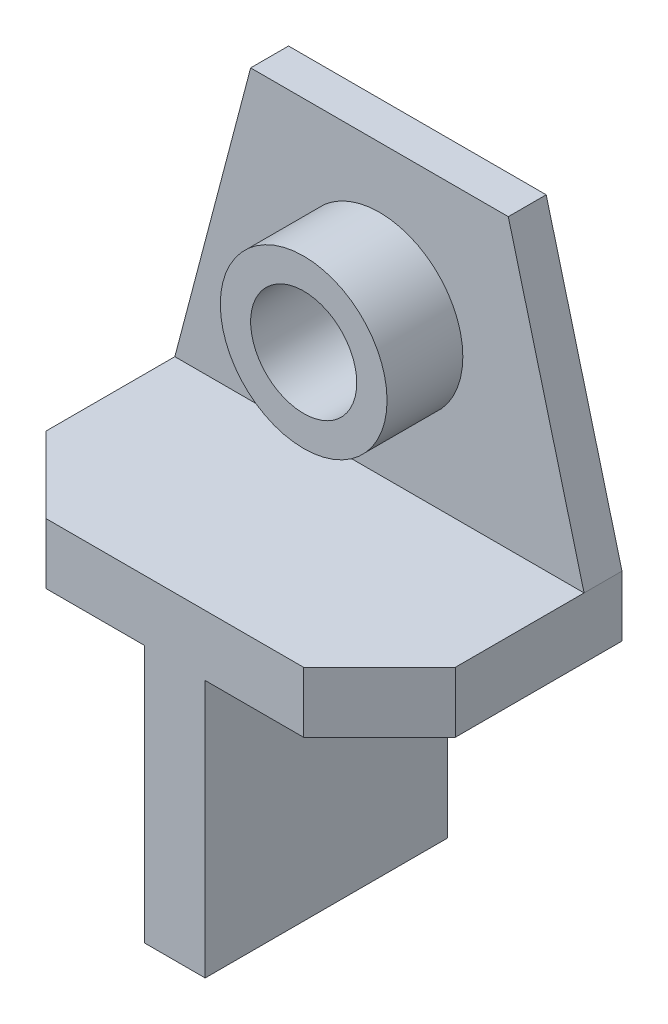
SolidWorks part; units mm, degrees
ref_plane "Front Plane" through (0, 0, 0) normal (0, 0, 1) x (1, 0, 0)
ref_plane "Top Plane" through (0, 0, 0) normal (0, 1, 0) x (1, 0, 0)
ref_plane "Right Plane" through (0, 0, 0) normal (1, 0, 0) x (0, 0, -1)
sketch "Sketch1" plane through (0, 0, 0) normal (0, 0, 1) x (1, 0, 0)
  line L0 (0, 0) -> (54, 0)
  line L1 (54, 0) -> (54, -8)
  line L2 (54, -8) -> (31, -8)
  line L3 (31, -8) -> (31, -42)
  line L4 (31, -42) -> (23, -42)
  line L5 (23, -42) -> (23, -8)
  line L6 (23, -8) -> (0, -8)
  line L7 (0, -8) -> (0, 0)
  point P3 (0, 0)
  point P10 (27, 0)
  point P11 (27, -42)
  dimension "D1" = 54
  dimension "D2" = 8
  dimension "D3" = 34
  dimension "D4" = 8
extrude "Boss-Extrude1" add sketch "Sketch1" along normal mid plane 32
sketch "Sketch2" plane through (0, 0, 16) normal (0, 0, 1) x (1, 0, 0)
  line L0 (0, 0) -> (10, 0)
  line L1 (54, 0) -> (0, 0) construction
  line L2 (10, 0) -> (10, -8)
  line L3 (0, -8) -> (23, -8) construction
  line L4 (10, -8) -> (0, -8)
  line L5 (0, -8) -> (0, 0)
  line L6 (54, 0) -> (44, 0)
  line L7 (44, 0) -> (44, -8)
  line L8 (31, -8) -> (54, -8) construction
  line L9 (44, -8) -> (54, -8)
  line L10 (54, -8) -> (54, 0)
  dimension "D1" = 10
  dimension "D2" = 10
extrude "Cut-Extrude1" [suppressed] cut sketch "Sketch2" against normal blind 10
sketch "Sketch3" plane through (0, 0, 0) normal (0, 1, 0) x (1, 0, 0)
  line L0 (0, 16) -> (54, 16)
  line L1 (54, 16) -> (0, 16) construction
  line L2 (54, 16) -> (54, 11)
  line L3 (54, -16) -> (54, 16) construction
  line L4 (54, 11) -> (0, 11)
  line L5 (0, -16) -> (0, 16) construction
  line L6 (0, 11) -> (0, 16)
  dimension "D1" = 5
extrude "Boss-Extrude2" add sketch "Sketch3" along normal blind 38
sketch "Sketch4" [suppressed] plane through (0, 0, -11) normal (0, 0, 1) x (1, 0, 0)
  line L0 (0, 38) -> (10, 38)
  line L1 (0, 38) -> (54, 38) construction
  line L2 (10, 38) -> (0, 0)
  line L3 (0, 0) -> (0, 38)
  line L4 (44, 38) -> (54, 38)
  line L5 (54, 38) -> (54, 0) construction
  line L6 (54, 38) -> (54, 0)
  line L7 (54, 0) -> (44, 0) construction
  line L8 (54, 0) -> (44, 38)
  point P11 (27, 38)
  dimension "D1" = 17
  dimension "D2" = 17
extrude "Cut-Extrude2" [suppressed] cut sketch "Sketch4" against normal through all
sketch "Sketch5" plane through (0, 0, 0) normal (0, 1, 0) x (1, 0, 0)
  line L0 (44, -16) -> (54, -6)
  line L1 (54, -16) -> (0, -16) construction
  line L2 (54, -16) -> (54, 11) construction
  line L3 (10, -16) -> (0, -6)
  line L4 (0, -16) -> (0, 11) construction
  line L5 (0, -6) -> (0, -16)
  line L6 (0, -16) -> (10, -16)
  line L7 (54, -6) -> (54, -16)
  line L8 (44, -16) -> (54, -16)
  dimension "D1" = 10
  dimension "D2" = 10
  dimension "D3" = 10
extrude "Cut-Extrude4" cut sketch "Sketch5" against normal blind 10
sketch "Sketch10" plane through (0, 0, -11) normal (0, 0, 1) x (1, 0, 0)
  line L0 (0, 38) -> (54, 38) construction
  circle A0 centre (27, 19) radius 11
  circle A1 centre (27, 19) radius 7
  point P5 (27, 38)
  dimension "D1" = 22
  dimension "D2" = 14
  dimension "D3" = 19
  dimension "D4" = 27
extrude "Boss-Extrude4" add sketch "Sketch10" along normal blind 10
sketch "Sketch12" plane through (0, 0, -11) normal (0, 0, 1) x (1, 0, 0)
  line L0 (0, 0) -> (10, 38)
  line L1 (0, 38) -> (54, 38) construction
  line L2 (10, 38) -> (0, 38)
  line L3 (0, 38) -> (0, 0)
  line L4 (44, 38) -> (54, 38)
  line L5 (54, 38) -> (54, 0)
  line L6 (54, 0) -> (44, 38)
  dimension "D1" = 10
  dimension "D2" = 10
extrude "Cut-Extrude5" cut sketch "Sketch12" against normal blind 10
